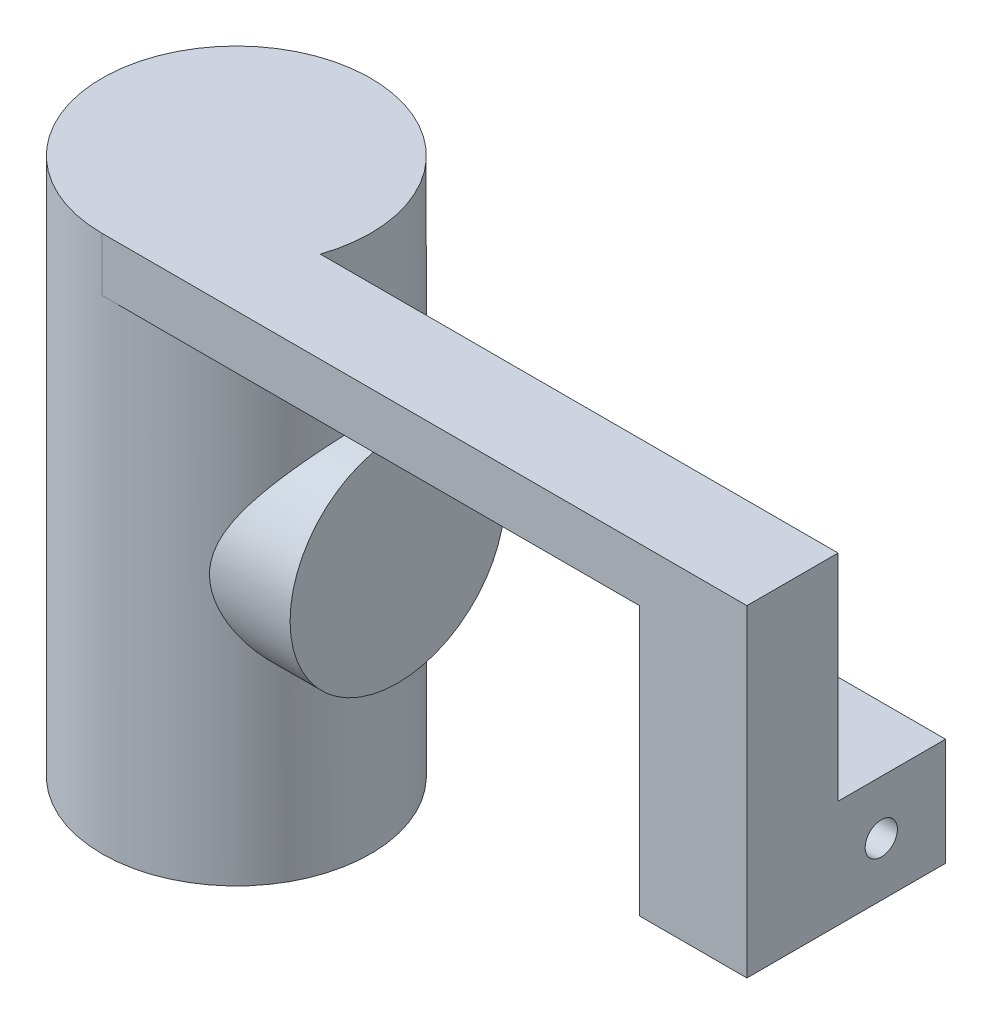
SolidWorks part; units mm, degrees
ref_plane "Front Plane" through (0, 0, 0) normal (0, 0, 1) x (1, 0, 0)
ref_plane "Top Plane" through (0, 0, 0) normal (0, 1, 0) x (1, 0, 0)
ref_plane "Right Plane" through (0, 0, 0) normal (1, 0, 0) x (0, 0, -1)
sketch "Sketch1" plane through (0, 0, 0) normal (0, 1, 0) x (1, 0, 0)
  circle A0 centre (0, 0) radius 25
  dimension "D1" = 50
extrude "Boss-Extrude1" add sketch "Sketch1" along normal mid plane 100
sketch "Sketch2" plane through (0, 0, 0) normal (1, 0, 0) x (0, 0, -1)
  circle A0 centre (0, 0) radius 20
  point P2 (0, 0)
  point P3 (0.9592, 17.6474)
  point P4 (0, 0)
  point P5 (0, 0)
  point P7 (0, 0)
  point P9 (0, 0)
  point P10 (0, 0)
  dimension "D1" = 40
extrude "Boss-Extrude2" add sketch "Sketch2" along normal blind 30
sketch "Sketch3" plane through (0, 0, 0) normal (1, 0, 0) x (0, 0, -1)
  line L1 (-25, 50) -> (-8.0391, 50)
  line L2 (-25, 50) -> (-25, 40)
  line L3 (-25, 40) -> (-8.0391, 40)
  line L4 (-8.0391, 50) -> (-8.0391, 40)
  dimension "D1" = 10
extrude "Boss-Extrude3" add sketch "Sketch3" along normal offset from surface (120 mm away) 90 up to face at (30, 0, -20) offset beyond the face yes
sketch "Sketch4" plane through (0, 40, 0) normal (0, -1, 0) x (1, 0, 0)
  line L0 (120, 8.0391) -> (23.6722, 8.0391) construction
  line L1 (120, 25) -> (100, 25)
  line L2 (120, 25) -> (120, 8.0391)
  line L3 (120, 8.0391) -> (100, 8.0391)
  line L4 (100, 25) -> (100, 8.0391)
  dimension "D1" = 20
extrude "Boss-Extrude4" add sketch "Sketch4" along normal blind 50
sketch "Sketch5" plane through (0, 0, 8.0391) normal (0, 0, -1) x (-1, 0, 0)
  line L0 (-120, -10) -> (-120, 50) construction
  line L1 (-100, -10) -> (-120, -10)
  line L2 (-100, -10) -> (-100, 10)
  line L3 (-100, 10) -> (-120, 10)
  line L4 (-120, -10) -> (-120, 10)
  dimension "D1" = 20
extrude "Boss-Extrude5" add sketch "Sketch5" along normal blind 20
sketch "Sketch6" plane through (120, 0, 0) normal (1, 0, 0) x (0, 0, -1)
  circle A0 centre (0, 0) radius 3
  point P2 (0, 0)
  point P4 (0, 0)
  dimension "D1" = 6
extrude "Cut-Extrude1" cut sketch "Sketch6" against normal up to surface (20 mm away) up to face at (100, 13.3333, 7.0261)
